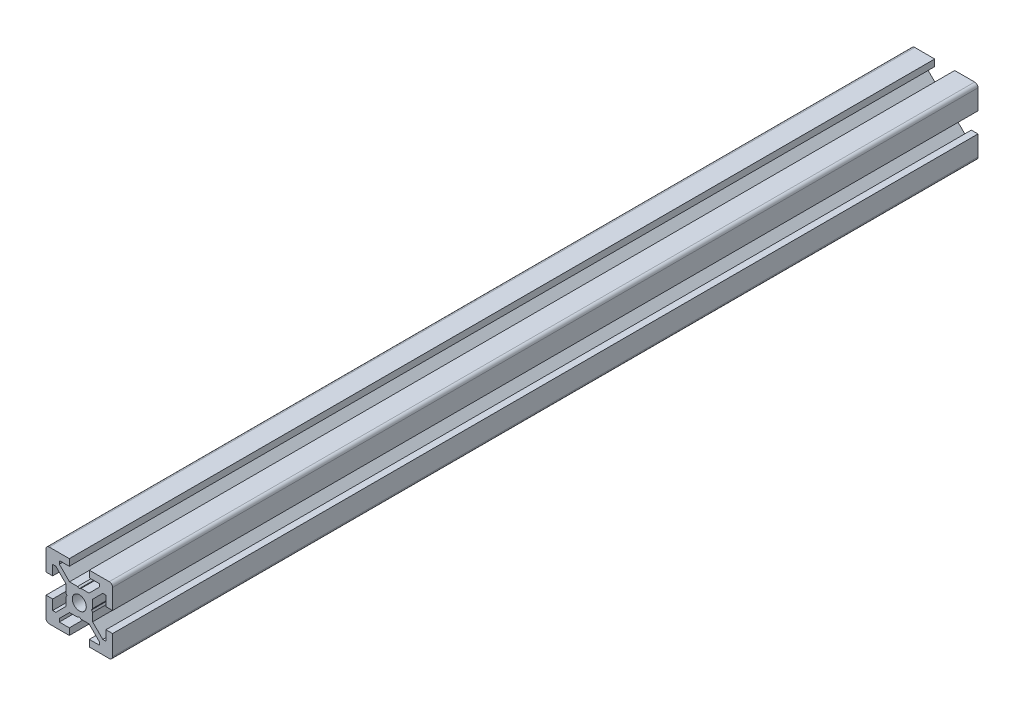
SolidWorks part; units mm, degrees
ref_plane "정면" through (0, 0, 0) normal (0, 0, 1) x (1, 0, 0)
ref_plane "윗면" through (0, 0, 0) normal (0, 1, 0) x (1, 0, 0)
ref_plane "우측면" through (0, 0, 0) normal (1, 0, 0) x (0, 0, -1)
sketch "Model" plane through (0, 0, 0) normal (0, 0, 1) x (1, 0, 0)
  line L0 (-10, 3) -> (-8, 3)
  line L1 (-10, 9) -> (-10, 3)
  line L2 (-3, 10) -> (-9, 10)
  line L3 (-3, 8) -> (-3, 10)
  line L4 (-6, 8) -> (-3, 8)
  line L5 (-6, 7.0607) -> (-6, 8)
  line L6 (-2.9393, 4) -> (-6, 7.0607)
  line L7 (-0.5196, 4) -> (-2.9393, 4)
  line L8 (0, 3.7) -> (-0.5196, 4)
  line L9 (0.5196, 4) -> (0, 3.7)
  line L10 (2.9393, 4) -> (0.5196, 4)
  line L11 (6, 7.0607) -> (2.9393, 4)
  line L12 (6, 8) -> (6, 7.0607)
  line L13 (3, 8) -> (6, 8)
  line L14 (3, 10) -> (3, 8)
  line L15 (9, 10) -> (3, 10)
  line L16 (10, 3) -> (10, 9)
  line L17 (8, 3) -> (10, 3)
  line L18 (8, 6) -> (8, 3)
  line L19 (7.0607, 6) -> (8, 6)
  line L20 (4, 2.9393) -> (7.0607, 6)
  line L21 (4, 0.5196) -> (4, 2.9393)
  line L22 (3.7, 0) -> (4, 0.5196)
  line L23 (4, -0.5196) -> (3.7, 0)
  line L24 (4, -2.9393) -> (4, -0.5196)
  line L25 (7.0607, -6) -> (4, -2.9393)
  line L26 (8, -6) -> (7.0607, -6)
  line L27 (8, -3) -> (8, -6)
  line L28 (10, -3) -> (8, -3)
  line L29 (10, -9) -> (10, -3)
  line L30 (3, -10) -> (9, -10)
  line L31 (3, -8) -> (3, -10)
  line L32 (6, -8) -> (3, -8)
  line L33 (6, -7.0607) -> (6, -8)
  line L34 (2.9393, -4) -> (6, -7.0607)
  line L35 (0.5196, -4) -> (2.9393, -4)
  line L36 (0, -3.7) -> (0.5196, -4)
  line L37 (-0.5196, -4) -> (0, -3.7)
  line L38 (-2.9393, -4) -> (-0.5196, -4)
  line L39 (-6, -7.0607) -> (-2.9393, -4)
  line L40 (-6, -8) -> (-6, -7.0607)
  line L41 (-3, -8) -> (-6, -8)
  line L42 (-3, -10) -> (-3, -8)
  line L43 (-9, -10) -> (-3, -10)
  line L44 (-10, -3) -> (-10, -9)
  line L45 (-8, -3) -> (-10, -3)
  line L46 (-8, -6) -> (-8, -3)
  line L47 (-7.0607, -6) -> (-8, -6)
  line L48 (-4, -2.9393) -> (-7.0607, -6)
  line L49 (-4, -0.5196) -> (-4, -2.9393)
  line L50 (-3.7, 0) -> (-4, -0.5196)
  line L51 (-4, 0.5196) -> (-3.7, 0)
  line L52 (-4, 2.9393) -> (-4, 0.5196)
  line L53 (-7.0607, 6) -> (-4, 2.9393)
  line L54 (-8, 6) -> (-7.0607, 6)
  line L55 (-8, 3) -> (-8, 6)
  arc A0 (-9, 10) -> (-10, 9) centre (-9, 9) ccw
  arc A1 (10, 9) -> (9, 10) centre (9, 9) ccw
  arc A2 (9, -10) -> (10, -9) centre (9, -9) ccw
  arc A3 (-10, -9) -> (-9, -10) centre (-9, -9) ccw
  circle A4 centre (0, 0) radius 2.1
  point P66 (0, 0)
  dimension "D1" = 4.2
extrude "보스-돌출1" add sketch "Model" along normal blind 260
